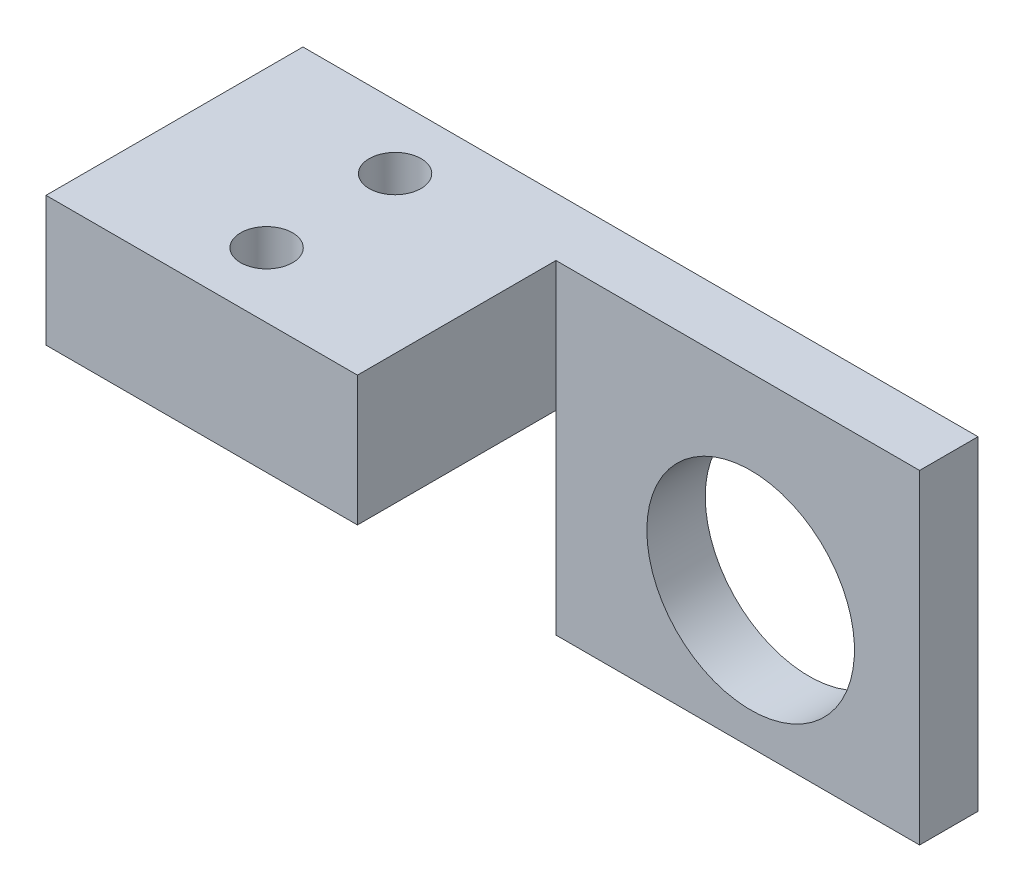
SolidWorks part; units mm, degrees
material "ABS"
ref_plane "Front Plane" through (0, 0, 0) normal (0, 0, 1) x (1, 0, 0)
ref_plane "Top Plane" through (0, 0, 0) normal (0, 1, 0) x (1, 0, 0)
ref_plane "Right Plane" through (0, 0, 0) normal (1, 0, 0) x (0, 0, -1)
sketch "Sketch1" plane through (0, 0, 0) normal (0, 0, 1) x (1, 0, 0)
  line L0 (-24, 15) -> (0, 15)
  line L1 (0, 15) -> (0, 0)
  line L2 (0, 0) -> (93, 0)
  line L3 (93, 0) -> (93, 102.7)
  line L4 (93, 102.7) -> (0, 102.7)
  line L5 (0, 102.7) -> (0, 30)
  line L6 (0, 30) -> (-24, 30)
  line L7 (-24, 30) -> (-24, 15)
  circle A0 centre (15, 10.5) radius 8
  circle A1 centre (70, 72) radius 11
  circle A2 centre (15, 10.5) radius 11
  dimension "D1" = 15
  dimension "D10" = 16
  dimension "D11" = 22
  dimension "D12" = 22
  dimension "D2" = 24
  dimension "D3" = 72.7
  dimension "D4" = 15
  dimension "D5" = 15
  dimension "D6" = 10.5
  dimension "D7" = 82.5061
  dimension "D8" = 72
  dimension "D9" = 93
extrude "Boss-Extrude1" add sketch "Sketch1" along normal blind 4.8 contours A2 L2 L3 L4 L5 L6 L7 L0 L1 A1 | L2 A2 A0
sketch "Sketch2" plane through (0, 0, 4.8) normal (0, 0, 1) x (1, 0, 0)
  line L0 (93, 0) -> (93, 102.7) construction
  line L1 (48.1786, 92.7632) -> (93, 92.7632)
  line L2 (48.1786, 92.7632) -> (48.1786, 52.666)
  line L3 (48.1786, 52.666) -> (93, 52.666)
  line L4 (93, 92.7632) -> (93, 52.666)
  line L5 (48.1786, 92.7632) -> (93, 52.666) construction
  line L6 (48.1786, 52.666) -> (93, 92.7632) construction
  circle A0 centre (70, 72) radius 11
  circle A1 centre (70, 72) radius 4.15
  point P8 (70.5893, 72.7146)
  line M4 (93, 0) -> (93, 102.7)
  circle M10 centre (70, 72) radius 11
  dimension "D1" = 22
  dimension "D2" = 8.3
extrude "Boss-Extrude2" add sketch "Sketch2" along normal blind 8.2 contours L2 L3 L1 M4 M10
sketch "Sketch3" plane through (0, 0, 4.8) normal (0, 0, 1) x (1, 0, 0)
  line L1 (-24, 15) -> (0, 15)
  line L2 (-24, 15) -> (-24, 30)
  line L3 (-24, 30) -> (0, 30)
  line L4 (0, 15) -> (0, 30)
  line L5 (-24, 15) -> (0, 30) construction
  line L6 (-24, 30) -> (0, 15) construction
  line L7 (0, 0) -> (93, 0)
  line L8 (0, 0) -> (0, 52.666)
  line L9 (0, 52.666) -> (93, 52.666)
  line L10 (93, 0) -> (93, 52.666)
  line L11 (0, 0) -> (93, 52.666) construction
  line L12 (0, 52.666) -> (93, 0) construction
  circle A0 centre (15, 10.5) radius 8
  point P4 (-12, 22.5)
  point P11 (46.5, 26.333)
  circle M1 centre (15, 10.5) radius 8
  line M6 (0, 102.7) -> (0, 30)
  line M7 (0, 30) -> (-24, 30)
  line M8 (-24, 30) -> (-24, 15)
  line M9 (-24, 15) -> (0, 15)
  line M10 (0, 15) -> (0, 0)
  line M11 (0, 0) -> (93, 0)
  line M12 (93, 0) -> (93, 52.666)
  line M13 (93, 52.666) -> (48.1786, 52.666)
extrude "Boss-Extrude3" add sketch "Sketch3" along normal blind 5 contours L4 M9 M7 M8 | L9 L4 M6 M10 M11 M12 M13 M1
sketch "Sketch4" plane through (0, 75.2347, 0) normal (0, -1, 0) x (1, 0, 0)
  line L0 (0, 9.8) -> (0, 4.8) construction
  line L1 (0, 4.8) -> (48.1786, 4.8)
  line L2 (0, 4.8) -> (0, 45.3)
  line L3 (0, 45.3) -> (48.1786, 45.3)
  line L4 (48.1786, 4.8) -> (48.1786, 45.3)
  line L5 (0, 4.8) -> (48.1786, 45.3) construction
  line L6 (0, 45.3) -> (48.1786, 4.8) construction
  line L7 (0, 4.8) -> (48.1786, 4.8) construction
  line L8 (48.1786, 13) -> (48.1786, 9.8) construction
  line L9 (0, 0) -> (93, 0) construction
  line L10 (0, 45.3) -> (-5, 45.3)
  line L11 (0, 45.3) -> (0, 0)
  line L12 (0, 0) -> (-5, 0)
  line L13 (-5, 45.3) -> (-5, 0)
  line L14 (0, 45.3) -> (-5, 0) construction
  line L15 (0, 0) -> (-5, 45.3) construction
  circle A0 centre (38.3604, 30.3) radius 6.35
  circle A1 centre (38.3604, 23.3) radius 18.5
  circle A3 centre (53.8604, 23.3) radius 2
  circle A4 centre (46.1104, 9.8766) radius 2
  circle A5 centre (30.6104, 9.8766) radius 2
  point P10 (24.0893, 25.05)
  point P30 (-2.5, 22.65)
  dimension "D1" = 12.7
  dimension "D2" = 15
  dimension "D3" = 4
  dimension "D4" = 4
  dimension "D5" = 4
  dimension "D6" = 5
  dimension "D7" = 0
extrude "Boss-Extrude4" add sketch "Sketch4" along normal blind 5
sketch "Sketch5" plane through (48.1786, 0, 0) normal (1, 0, 0) x (0, 0, -1)
  line L0 (-45.3, 75.2347) -> (-13, 92.7632)
  line L1 (-13, 92.7632) -> (-4.8, 92.7632)
  line L2 (-4.8, 92.7632) -> (-4.8, 70.2347)
  line L3 (-4.8, 70.2347) -> (-45.3, 70.2347)
  line L4 (-45.3, 70.2347) -> (-45.3, 75.2347)
extrude "Boss-Extrude5" add sketch "Sketch5" against normal blind 5
sketch "Sketch6" plane through (0, 0, 4.8) normal (0, 0, 1) x (1, 0, 0)
  line L0 (0, 70.2347) -> (0, 52.666) construction
  line L1 (0, 70.2347) -> (48.1786, 70.2347)
  line L2 (0, 70.2347) -> (0, 52.666)
  line L3 (0, 52.666) -> (48.1786, 52.666)
  line L4 (48.1786, 70.2347) -> (48.1786, 52.666)
  line L5 (0, 70.2347) -> (48.1786, 52.666) construction
  line L6 (0, 52.666) -> (48.1786, 70.2347) construction
  line L7 (0, 70.2347) -> (48.1786, 70.2347) construction
  point P4 (24.0893, 61.4504)
extrude "Boss-Extrude6" add sketch "Sketch6" along normal up to surface (5 mm away)
sketch "Sketch8" plane through (0, 30, 0) normal (0, 1, 0) x (1, 0, 0)
  line L0 (0, 0) -> (-24, -9.8)
  line L1 (-24, -9.8) -> (-24, 0)
  line L2 (-24, 0) -> (0, -9.8)
  circle A0 centre (-12, -4.9) radius 2
  dimension "D1" = 4
extrude "Cut-Extrude1" cut sketch "Sketch8" against normal through all contours A0
sketch "Sketch9" plane through (0, 0, 0) normal (0, 0, -1) x (-1, 0, 0)
  line L0 (0, 0) -> (-93, 0) construction
  line L1 (-93, 102.7) -> (-28.0185, 102.7)
  line L2 (-93, 102.7) -> (-93, 0)
  line L3 (-93, 0) -> (-28.0185, 0)
  line L4 (-28.0185, 102.7) -> (-28.0185, 0)
extrude "Cut-Extrude2" cut sketch "Sketch9" against normal blind 200
sketch "Sketch13" plane through (0, 0, 0) normal (-1, 0, 0) x (0, 0, 1)
  line L0 (9.8, 30) -> (0, 30) construction
  line L1 (0, 102.7) -> (48.03, 102.7)
  line L2 (0, 102.7) -> (0, 30)
  line L3 (0, 30) -> (48.03, 30)
  line L4 (48.03, 102.7) -> (48.03, 30)
  dimension "D1" = 0
extrude "Cut-Extrude5" cut sketch "Sketch13" against normal blind 100
sketch "Sketch14" plane through (0, 0, 9.8) normal (0, 0, 1) x (1, 0, 0)
  line L0 (28.0185, 30) -> (28.0185, 0) construction
  line L1 (-24, 30) -> (28.0185, 30)
  line L2 (-24, 30) -> (-24, 25)
  line L3 (-24, 25) -> (28.0185, 25)
  line L4 (28.0185, 30) -> (28.0185, 25)
  line L6 (-24, 15) -> (0, 15) construction
  dimension "D1" = 10
extrude "Cut-Extrude6" cut sketch "Sketch14" against normal blind 100
sketch "Sketch15" plane through (0, 0, 9.8) normal (0, 0, 1) x (1, 0, 0)
  line L1 (-24, 25) -> (0, 25)
  line L2 (-24, 25) -> (-24, 15)
  line L3 (-24, 15) -> (0, 15)
  line L4 (0, 25) -> (0, 15)
extrude "Boss-Extrude7" add sketch "Sketch15" along normal blind 10
sketch "Sketch16" plane through (0, 25, 0) normal (0, 1, 0) x (1, 0, 0)
  line L0 (0, -19.8) -> (-24, -19.8) construction
  circle A0 centre (-12, -14.8) radius 2
  circle A1 centre (-12, -4.9) radius 2 construction
  dimension "D1" = 4
  dimension "D2" = 5
  dimension "D3" = 0
extrude "Cut-Extrude7" cut sketch "Sketch16" against normal blind 10
sketch "Sketch17" plane through (0, 25, 0) normal (0, 1, 0) x (1, 0, 0)
  line L0 (28.0185, 0) -> (28.0185, -9.8) construction
  line L1 (0, -9.8) -> (28.0185, -9.8)
  line L2 (0, -9.8) -> (0, -4.5)
  line L3 (0, -4.5) -> (28.0185, -4.5)
  line L4 (28.0185, -9.8) -> (28.0185, -4.5)
  line L5 (-24, 0) -> (28.0185, 0) construction
  dimension "D1" = 4.5
extrude "Cut-Extrude11" cut sketch "Sketch17" against normal blind 100
